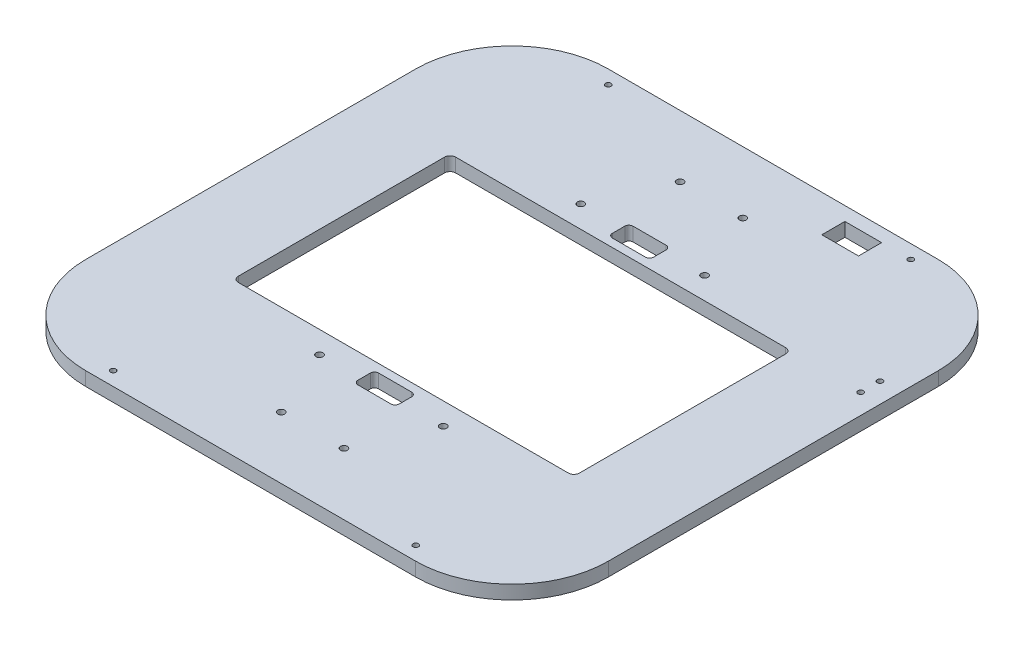
SolidWorks part; units mm, degrees
ref_plane "Plano frontal" through (0, 0, 0) normal (0, 0, 1) x (1, 0, 0)
ref_plane "Plano superior" through (0, 0, 0) normal (0, 1, 0) x (1, 0, 0)
ref_plane "Plano direito" through (0, 0, 0) normal (1, 0, 0) x (0, 0, -1)
sketch "Esboço1" plane through (0, 0, 0) normal (0, 1, 0) x (1, 0, 0)
  line L1 (-95, -95) -> (95, -95)
  line L2 (-95, -95) -> (-95, 95)
  line L3 (-95, 95) -> (95, 95)
  line L4 (95, -95) -> (95, 95)
  line L5 (-95, -95) -> (95, 95) construction
  line L6 (-95, 95) -> (95, -95) construction
  point P0 (0, 0)
  dimension "D1" = 190
  dimension "D2" = 190
extrude "Ressalto-extrusão1" add sketch "Esboço1" along normal blind 5
fillet "Filete1" radius 35 4 edges at (95, 2.5, -95) (95, 2.5, 95) (-95, 2.5, -95) (-95, 2.5, 95)
sketch "Esboço2" plane through (0, 5, 0) normal (0, 1, 0) x (1, 0, 0)
  line L2 (0, 95) -> (0, -95) construction
  line L4 (-95, 0) -> (95, 0) construction
  line L6 (-95, 60) -> (-95, -60) construction
  line L7 (95, -60) -> (95, 60) construction
  line L8 (-60, -95) -> (60, -95) construction
  line L9 (60, 95) -> (-60, 95) construction
  circle A0 centre (-55, 90) radius 1
  circle A1 centre (55, 90) radius 1
  circle A2 centre (55, -90) radius 1
  circle A3 centre (-55, -90) radius 1
  dimension "D1" = 2
  dimension "D2" = 110
  dimension "D3" = 180
extrude "Corte-extrusão1" cut sketch "Esboço2" against normal through all
sketch "Esboço3" plane through (0, 5, 0) normal (0, 1, 0) x (1, 0, 0)
  line L1 (-60, 39.5) -> (60, 39.5)
  line L2 (-62, 37.5) -> (-62, -37.5)
  line L3 (-60, -39.5) -> (60, -39.5)
  line L4 (62, 37.5) -> (62, -37.5)
  line L5 (-62, 39.5) -> (62, -39.5) construction
  line L6 (-62, -39.5) -> (62, 39.5) construction
  arc A0 (-60, -39.5) -> (-62, -37.5) centre (-60, -37.5) cw
  arc A1 (60, -39.5) -> (62, -37.5) centre (60, -37.5) ccw
  arc A2 (62, 37.5) -> (60, 39.5) centre (60, 37.5) ccw
  arc A3 (-62, 37.5) -> (-60, 39.5) centre (-60, 37.5) cw
  point P0 (0, 0)
  dimension "D3" = 2
  dimension "D1" = 124
  dimension "D2" = 79
extrude "Corte-extrusão2" cut sketch "Esboço3" against normal blind 10
sketch "Sketch3" plane through (0, 5, 0) normal (0, 1, 0) x (1, 0, 0)
  line L0 (-95, 0) -> (95, 0) construction
  line L1 (-95, 60) -> (-95, -60) construction
  line L2 (95, -60) -> (95, 60) construction
  line L3 (0, 95) -> (0, -95) construction
  line L4 (60, 95) -> (-60, 95) construction
  line L5 (-60, -95) -> (60, -95) construction
  circle A0 centre (22.5031, 47.5) radius 1.25
  circle A1 centre (-22.4969, 47.5) radius 1.25
  circle A2 centre (-11.3969, 72.5) radius 1.25
  circle A3 centre (11.4031, 72.5) radius 1.25
  circle A4 centre (11.4031, -72.5) radius 1.25
  circle A5 centre (-11.3969, -72.5) radius 1.25
  circle A6 centre (-22.4969, -47.5) radius 1.25
  circle A7 centre (22.5031, -47.5) radius 1.25
  dimension "D1" = 22.5031
  dimension "D2" = 22.4969
extrude "Cut-Extrude1" cut sketch "Sketch3" against normal through all
sketch "Sketch5" plane through (0, 5, 0) normal (0, 1, 0) x (1, 0, 0)
  circle A0 centre (87.7056, 46.0885) radius 1
  circle A1 centre (87.7056, 39.0705) radius 1
extrude "Cut-Extrude3" cut sketch "Sketch5" against normal through all
sketch "Sketch7" plane through (0, 5, 0) normal (0, 1, 0) x (1, 0, 0)
  line L0 (60, 95) -> (-60, 95) construction
  line L1 (44.3863, 81.6) -> (31.0363, 81.6)
  line L2 (44.3863, 81.6) -> (44.3863, 90)
  line L3 (44.3863, 90) -> (31.0363, 90)
  line L4 (31.0363, 81.6) -> (31.0363, 90)
  dimension "D1" = 8.4
  dimension "D2" = 13.35
  dimension "D3" = 5
extrude "Cut-Extrude5" cut sketch "Sketch7" against normal through all contours L2 L3 L4 L1
sketch "Sketch8" plane through (0, 5, 0) normal (0, 1, 0) x (1, 0, 0)
  line L0 (95, 0) -> (-95, 0) construction
  line L1 (6.0031, -50) -> (-5.9969, -50)
  line L2 (7.5031, -48.5) -> (7.5031, -44)
  line L3 (6.0031, -42.5) -> (-5.9969, -42.5)
  line L4 (-7.4969, -48.5) -> (-7.4969, -44)
  line L5 (95, -60) -> (95, 60) construction
  line L6 (-95, 60) -> (-95, -60) construction
  line L7 (-7.4969, 48.5) -> (-7.4969, 44)
  line L8 (6.0031, 42.5) -> (-5.9969, 42.5)
  line L9 (7.5031, 48.5) -> (7.5031, 44)
  line L10 (6.0031, 50) -> (-5.9969, 50)
  arc A0 (-5.9969, -50) -> (-7.4969, -48.5) centre (-5.9969, -48.5) cw
  arc A1 (6.0031, -50) -> (7.5031, -48.5) centre (6.0031, -48.5) ccw
  arc A2 (6.0031, 50) -> (7.5031, 48.5) centre (6.0031, 48.5) cw
  arc A3 (-5.9969, 50) -> (-7.4969, 48.5) centre (-5.9969, 48.5) ccw
  arc A4 (7.5031, -44) -> (6.0031, -42.5) centre (6.0031, -44) ccw
  arc A5 (-5.9969, -42.5) -> (-7.4969, -44) centre (-5.9969, -44) ccw
  arc A6 (-7.4969, 44) -> (-5.9969, 42.5) centre (-5.9969, 44) ccw
  arc A7 (6.0031, 42.5) -> (7.5031, 44) centre (6.0031, 44) ccw
  point P10 (7.5031, -50)
  point P27 (7.5031, -42.5)
  point P30 (-7.4969, -42.5)
  point P33 (-7.4969, 42.5)
  point P36 (7.5031, 42.5)
  dimension "D1" = 1.5
  dimension "D4" = 1.5
  dimension "D5" = 1.5
  dimension "D2" = 6
  dimension "D3" = 6
extrude "Cut-Extrude6" cut sketch "Sketch8" against normal through all
